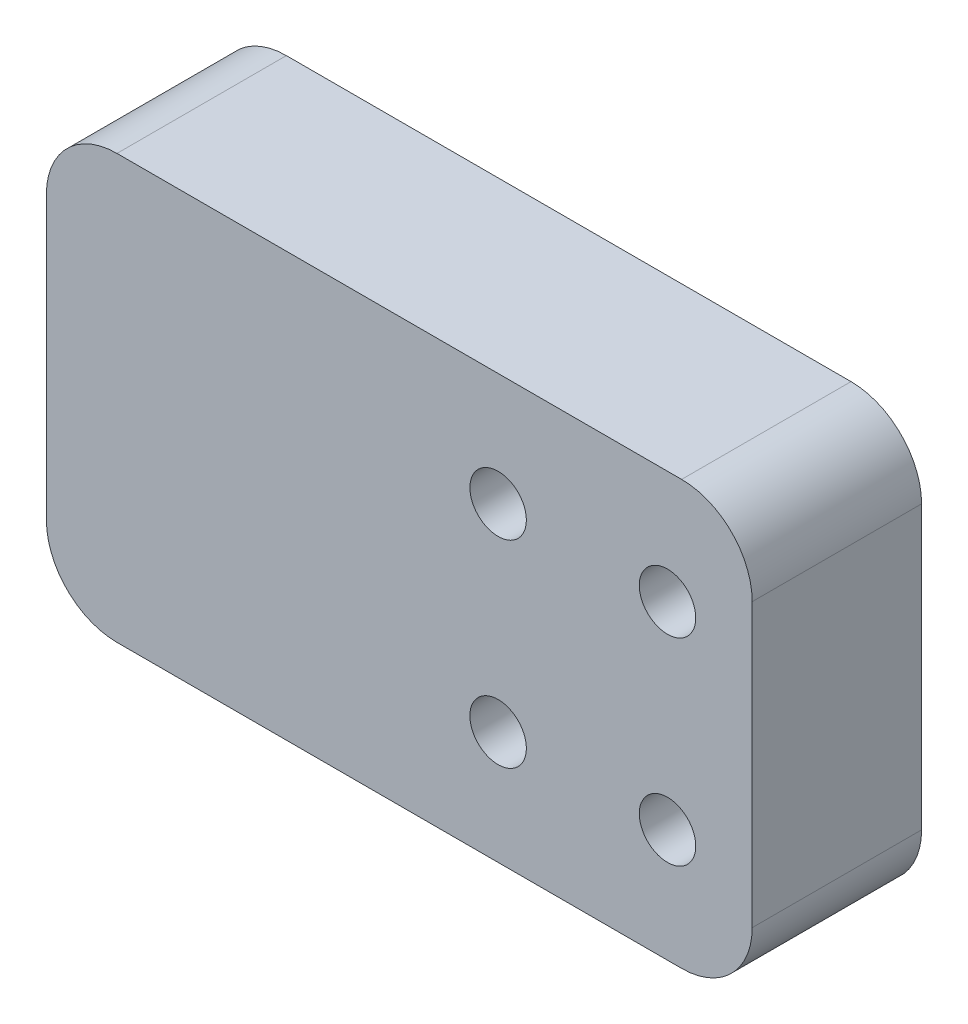
SolidWorks part; units mm, degrees
material "AISI 304"
ref_plane "前视基准面" through (0, 0, 0) normal (0, 0, 1) x (1, 0, 0)
ref_plane "上视基准面" through (0, 0, 0) normal (0, 1, 0) x (1, 0, 0)
ref_plane "右视基准面" through (0, 0, 0) normal (1, 0, 0) x (0, 0, -1)
other "Configuration Table"
sketch "草图1" plane through (0, 0, 0) normal (0, 0, 1) x (1, 0, 0)
  line L1 (0, 0) -> (50, 0)
  line L2 (0, 0) -> (0, 30)
  line L3 (0, 30) -> (50, 30)
  line L4 (50, 0) -> (50, 30)
  dimension "D1" = 50
  dimension "D2" = 30
extrude "凸台-拉伸1" add sketch "草图1" against normal blind 12
sketch "草图2" plane through (0, 0, 0) normal (0, 0, 1) x (1, 0, 0)
  line L0 (0, 15) -> (57.83, 15) construction
  line L1 (0, 30) -> (0, 0) construction
  line L2 (50, 0) -> (50, 30) construction
  circle A0 centre (44, 22) radius 2
  circle A1 centre (44, 8) radius 2
  circle A2 centre (32, 22) radius 2
  circle A3 centre (32, 8) radius 2
  dimension "D1" = 4
  dimension "D2" = 14
  dimension "D4" = 12
  dimension "D5" = 6
  dimension "D3" = 2
extrude "切除-拉伸1" cut sketch "草图2" against normal blind 12
fillet "圆角1" radius 5 4 edges at (0, 0, -6) (50, 30, -6) (0, 30, -6) (50, 0, -6)
